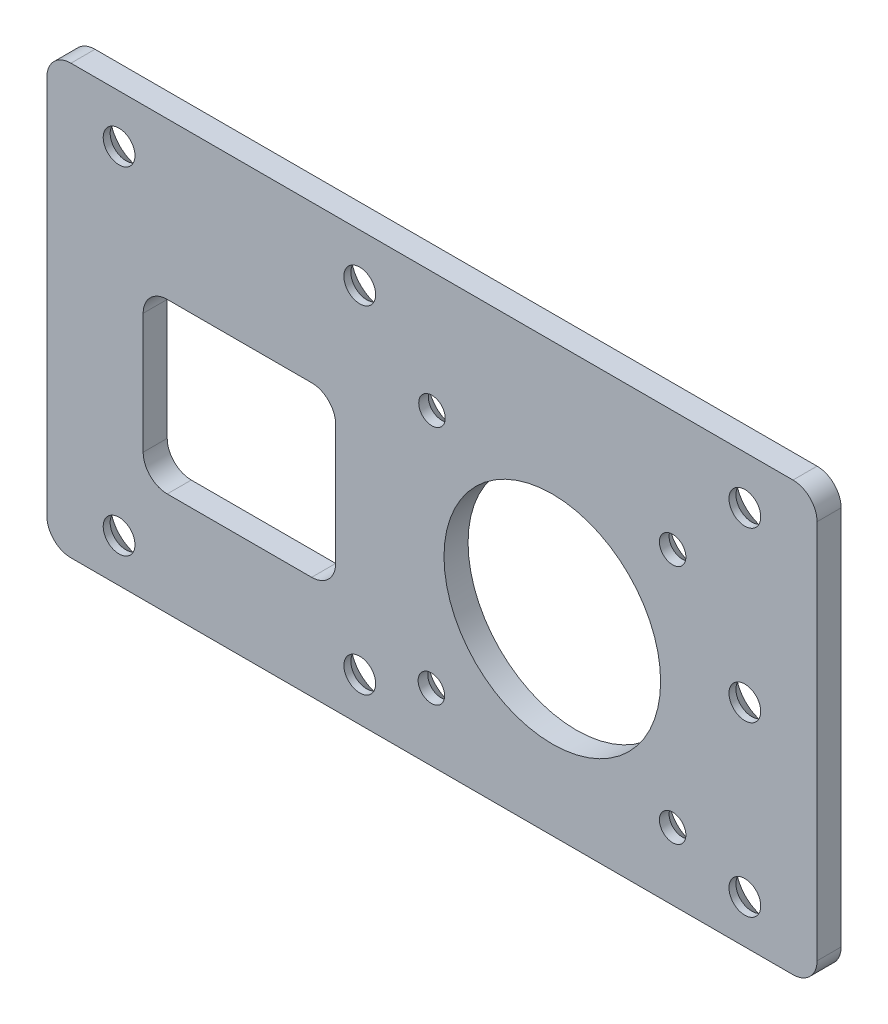
SolidWorks part; units mm, degrees
material "Ti-5Al-2.5Sn Отожженный (SS)"
ref_plane "Спереди" through (0, 0, 0) normal (0, 0, 1) x (1, 0, 0)
ref_plane "Сверху" through (0, 0, 0) normal (0, 1, 0) x (1, 0, 0)
ref_plane "Справа" through (0, 0, 0) normal (1, 0, 0) x (0, 0, -1)
sketch "Эскиз1" plane through (0, 0, 0) normal (0, 0, 1) x (1, 0, 0)
  line L0 (-105, 50) -> (55, 50)
  line L2 (0, 29.5) -> (0, -42.0296) construction
  line L3 (29.5, 0) -> (-35.0186, 0) construction
  line L4 (-105, -39) -> (55, -39)
  line L5 (-105, -39) -> (-105, 50)
  line L7 (55, -39) -> (55, 50)
  dimension "D1" = 89
  dimension "D4" = 160
  dimension "D2" = 55
  dimension "D3" = 39
  dimension "D5" = 90
extrude "Бобышка-Вытянуть1" add sketch "Эскиз1" along normal blind 5
sketch "Эскиз2" plane through (0, 0, 5) normal (0, 0, 1) x (1, 0, 0)
  circle A0 centre (0, 0) radius 22.5
  dimension "D1" = 45
extrude "Вырез-Вытянуть1" cut sketch "Эскиз2" against normal blind 10
sketch "Эскиз8" plane through (0, 0, 0) normal (0, 0, -1) x (-1, 0, 0)
  line L0 (105, -39) -> (-55, -39) construction
  line L1 (-40, 40) -> (90, 40) construction
  line L4 (-55, 50) -> (105, 50) construction
  line L5 (-55, -39) -> (-55, 50) construction
  point P0 (-40, -30)
  point P3 (-40, 5)
  point P6 (-40, 40)
  point P9 (40, 40)
  point P12 (40, -30)
  point P15 (90, -30)
  point P18 (90, 40)
  dimension "D1" = 9
  dimension "D2" = 70
  dimension "D3" = 35
  dimension "D4" = 80
  dimension "D5" = 130
  dimension "D6" = 15
hole_wizard "Зенковка для винта с потайной головкой и внутренним шестигранником M61" positions "Эскиз8" profile "Эскиз7" countersink size "M6" standard "DIN" end condition through all
sketch "Эскиз7" plane through (40, -30, 0) normal (1, 0, 0) x (0, 1, 0)
  line L0 (0, 0) -> (0, 5)
  line L1 (0, 5) -> (3.3, 5)
  line L2 (3.3, 5) -> (3.3, 3.555)
  line L3 (3.3, 3.555) -> (6.855, 0)
  line L5 (6.855, 0) -> (0, 0)
  line L6 (-3.3, 3.555) -> (-6.855, 0) construction
  line L11 (0, -6.35) -> (0, 107.95) construction
  dimension "Диаметр сквозного отверстия" = 6.6
  dimension "Глубина сквозного отверстия" = 5
  dimension "Диаметр передней зенковки" = 13.71
  dimension "Угол передней зенковки" = 90
sketch "Эскиз11" plane through (0, 0, 0) normal (0, 0, -1) x (-1, 0, 0)
  line L0 (-24.9129, 25) -> (-50024.9129, 25) construction
  line L1 (-25, 25.0621) -> (-25, -49974.9379) construction
  line L2 (-24.9129, -25) -> (49975.0871, -25) construction
  line L3 (25, -25.0621) -> (25, 49974.9379) construction
  point P0 (-25, 25)
  point P12 (-25, -25)
  point P14 (25.1249, -25)
  point P16 (25, 25)
  dimension "D1" = 50
  dimension "D2" = 50
  dimension "D3" = 25
  dimension "D4" = 25
hole_wizard "Зенковка для винта с потайной головкой и внутренним шестигранником M51" positions "Эскиз11" profile "Эскиз10" countersink size "M5" standard "DIN" end condition through all
sketch "Эскиз10" plane through (25, 25, 0) normal (1, 0, 0) x (0, 1, 0)
  line L0 (0, 0) -> (0, 5)
  line L1 (0, 5) -> (2.75, 5)
  line L2 (2.75, 5) -> (2.75, 2.985)
  line L3 (2.75, 2.985) -> (5.735, 0)
  line L5 (5.735, 0) -> (0, 0)
  line L6 (-2.75, 2.985) -> (-5.735, 0) construction
  line L11 (0, -6.35) -> (0, 107.95) construction
  dimension "Диаметр сквозного отверстия" = 5.5
  dimension "Глубина сквозного отверстия" = 5
  dimension "Диаметр передней зенковки" = 11.47
  dimension "Угол передней зенковки" = 90
sketch "Эскиз12" plane through (0, 0, 0) normal (0, 0, -1) x (-1, 0, 0)
  line L0 (0, 0) -> (50000, 0) construction
  line L1 (85, -17.5) -> (45, -17.5)
  line L2 (85, -17.5) -> (85, 17.5)
  line L3 (85, 17.5) -> (45, 17.5)
  line L4 (45, -17.5) -> (45, 17.5)
  line L5 (85, -17.5) -> (45, 17.5) construction
  line L6 (85, 17.5) -> (45, -17.5) construction
  point P0 (65, 0)
  dimension "D1" = 65
  dimension "D2" = 40
  dimension "D3" = 35
extrude "Вырез-Вытянуть2" cut sketch "Эскиз12" against normal blind 10
fillet "Скругление1" radius 5 8 edges at (-105, -39, 2.5) (-105, 50, 2.5) (55, -39, 2.5) (55, 50, 2.5) (-85, -17.5, 2.5) (-85, 17.5, 2.5) (-45, -17.5, 2.5) (-45, 17.5, 2.5)
